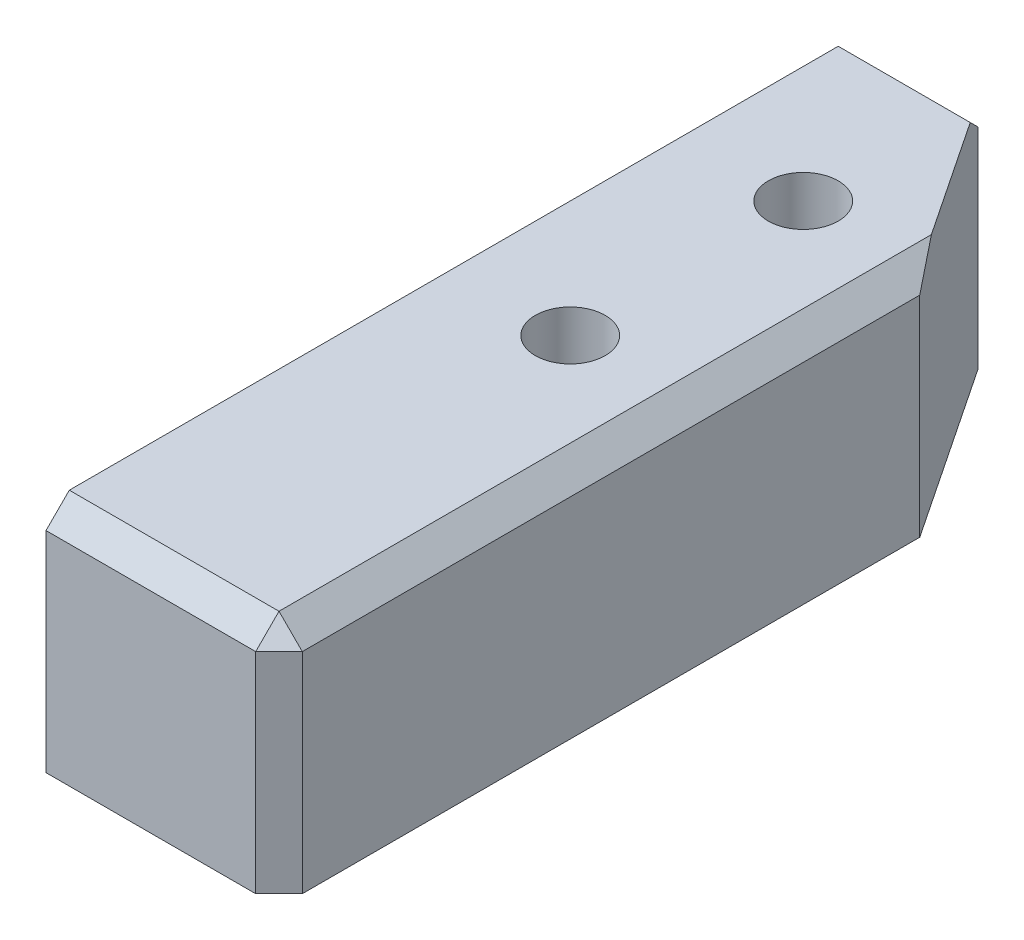
SolidWorks part; units mm, degrees
ref_plane "Front" through (0, 0, 0) normal (0, 0, 1) x (1, 0, 0)
ref_plane "Top" through (0, 0, 0) normal (0, 1, 0) x (1, 0, 0)
ref_plane "Right" through (0, 0, 0) normal (1, 0, 0) x (0, 0, -1)
sketch "草图1" plane through (0, 0, 0) normal (0, 1, 0) x (1, 0, 0)
  line L1 (5, -22.5) -> (-5, -22.5)
  line L2 (5, -22.5) -> (5, 12.5)
  line L3 (5, 12.5) -> (-5, 12.5)
  line L4 (-5, -22.5) -> (-5, 12.5)
  dimension "D1" = 10
  dimension "D2" = 35
extrude "凸台-拉伸1" add sketch "草图1" along normal blind 10
sketch "草图2" plane through (0, 10, 0) normal (0, 1, 0) x (1, 0, 0)
  line L0 (0, 12.5) -> (0, -22.5) construction
  line L1 (5, 12.5) -> (-5, 12.5) construction
  line L2 (-5, -22.5) -> (5, -22.5) construction
  circle A0 centre (0, 5) radius 1.5
  circle A1 centre (0, -5) radius 1.5
  dimension "D1" = 3
  dimension "D2" = 3
  dimension "D3" = 10
  dimension "D4" = 17.5
extrude "切除-拉伸1" cut sketch "草图2" against normal through all
sketch "草图3" plane through (0, 10, 0) normal (0, 1, 0) x (1, 0, 0)
  line L0 (0, 12.5) -> (5, 5)
  line L1 (5, 12.5) -> (-5, 12.5) construction
  line L2 (5, -22.5) -> (5, 12.5) construction
  line L3 (5, 5) -> (5, 12.5)
  line L4 (5, 12.5) -> (0, 12.5)
  dimension "D1" = 5
  dimension "D2" = 7.5
extrude "切除-拉伸2" cut sketch "草图3" against normal through all
chamfer "倒角1" distance 1 angle 45 5 edges at (5, 5, 22.5) (-2.5, 10, -12.5) (2.5, 10, -8.75) (5, 10, 8.75) (0, 10, 22.5)
